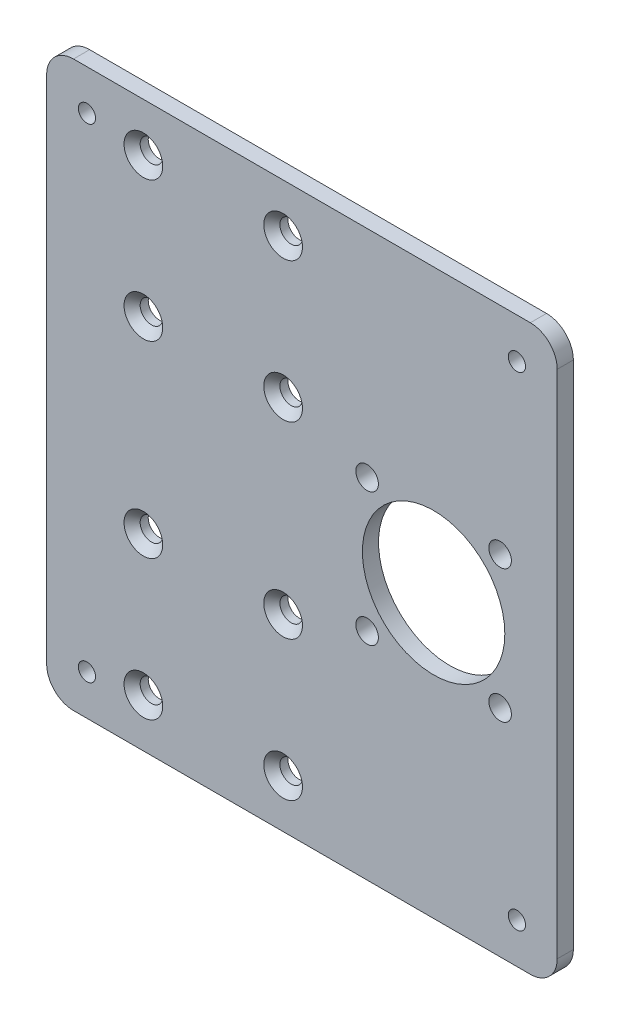
SolidWorks part; units mm, degrees
ref_plane "正面" through (0, 0, 0) normal (0, 0, 1) x (1, 0, 0)
ref_plane "平面" through (0, 0, 0) normal (0, 1, 0) x (1, 0, 0)
ref_plane "右側面" through (0, 0, 0) normal (1, 0, 0) x (0, 0, -1)
sketch "ｽｹｯﾁ2" plane through (0, 0, 0) normal (0, 0, 1) x (1, 0, 0)
  line L0 (-31, 0) -> (64, 0) construction
  line L1 (-13, -17.5) -> (13, -17.5) construction
  line L2 (-13, -17.5) -> (-13, -43.5) construction
  line L3 (-13, -43.5) -> (13, -43.5) construction
  line L4 (13, -17.5) -> (13, -43.5) construction
  line L5 (-13, -17.5) -> (13, -43.5) construction
  line L6 (-13, -43.5) -> (13, -17.5) construction
  line L7 (-31, -52.5) -> (64, -52.5)
  line L8 (-31, -52.5) -> (-31, 52.5)
  line L9 (-31, 52.5) -> (64, 52.5)
  line L10 (64, -52.5) -> (64, 52.5)
  line L11 (28.6256, 12.3744) -> (53.3744, -12.3744) construction
  line L12 (53.3744, 12.3744) -> (28.6256, -12.3744) construction
  line L13 (0, 30.5) -> (0, -30.5) construction
  line L14 (-23.5, -45) -> (56.5, -45) construction
  line L15 (-23.5, -45) -> (-23.5, 45) construction
  line L16 (-23.5, 45) -> (56.5, 45) construction
  line L17 (56.5, -45) -> (56.5, 45) construction
  line L18 (-23.5, -45) -> (56.5, 45) construction
  line L19 (-23.5, 45) -> (56.5, -45) construction
  line L20 (-15, -52.5) -> (15, -52.5) construction
  line L21 (-15, -52.5) -> (-15, 52.5) construction
  line L22 (-15, 52.5) -> (15, 52.5) construction
  line L23 (15, -52.5) -> (15, 52.5) construction
  line L24 (-15, -52.5) -> (15, 52.5) construction
  line L25 (-15, 52.5) -> (15, -52.5) construction
  line L26 (-13, 43.5) -> (13, 17.5) construction
  line L27 (13, 43.5) -> (-13, 17.5) construction
  circle A0 centre (-13, -17.5) radius 2.1
  circle A1 centre (-13, -43.5) radius 2.1
  circle A2 centre (13, -17.5) radius 2.1
  circle A3 centre (13, -43.5) radius 2.1
  circle A4 centre (41, 0) radius 13.25
  circle A5 centre (53.3744, 12.3744) radius 2.1
  circle A6 centre (28.6256, -12.3744) radius 2.1
  circle A7 centre (53.3744, -12.3744) radius 2.1
  circle A8 centre (28.6256, 12.3744) radius 2.1
  circle A10 centre (-23.5, 45) radius 1.6
  circle A11 centre (-23.5, -45) radius 1.6
  circle A12 centre (56.5, -45) radius 1.6
  circle A13 centre (56.5, 45) radius 1.6
  circle A14 centre (41, 0) radius 23 construction
  circle A15 centre (41, 0) radius 17.5 construction
  circle A16 centre (-13, 17.5) radius 2.1
  circle A17 centre (13, 17.5) radius 2.1
  circle A18 centre (13, 43.5) radius 2.1
  circle A19 centre (-13, 43.5) radius 2.1
  point P0 (0, 0)
  point P19 (41, 0)
  point P24 (41, 0)
  point P29 (16.5, 0)
  point P38 (0, 0)
  point P49 (0, 0)
  point P50 (0, 30.5)
  point P53 (0, 30.5)
  dimension "D1" = 4.2
  dimension "D3" = 26.5
  dimension "D4" = 4.2
  dimension "D7" = 46
  dimension "D8" = 7.5
  dimension "D12" = 26
  dimension "D14" = 3.2
  dimension "D15" = 35
  dimension "D5" = 35
  dimension "D2" = 26
  dimension "D6" = 45
  dimension "D9" = 7.5
  dimension "D10" = 90
  dimension "D11" = 30
  dimension "D13" = 80
extrude "ﾎﾞｽ - 押し出し1" add sketch "ｽｹｯﾁ2" along normal blind 3
fillet "ﾌｨﾚｯﾄ1" radius 5 4 edges at (-31, -52.5, 1.5) (64, -52.5, 1.5) (-31, 52.5, 1.5) (64, 52.5, 1.5)
chamfer "面取り1" distance 1.5 angle 45 8 edges at (15.1, 43.5, 3) (-10.9, 43.5, 3) (-10.9, 17.5, 3) (15.1, 17.5, 3) (-10.9, -17.5, 3) (15.1, -17.5, 3) (15.1, -43.5, 3) (-10.9, -43.5, 3)
